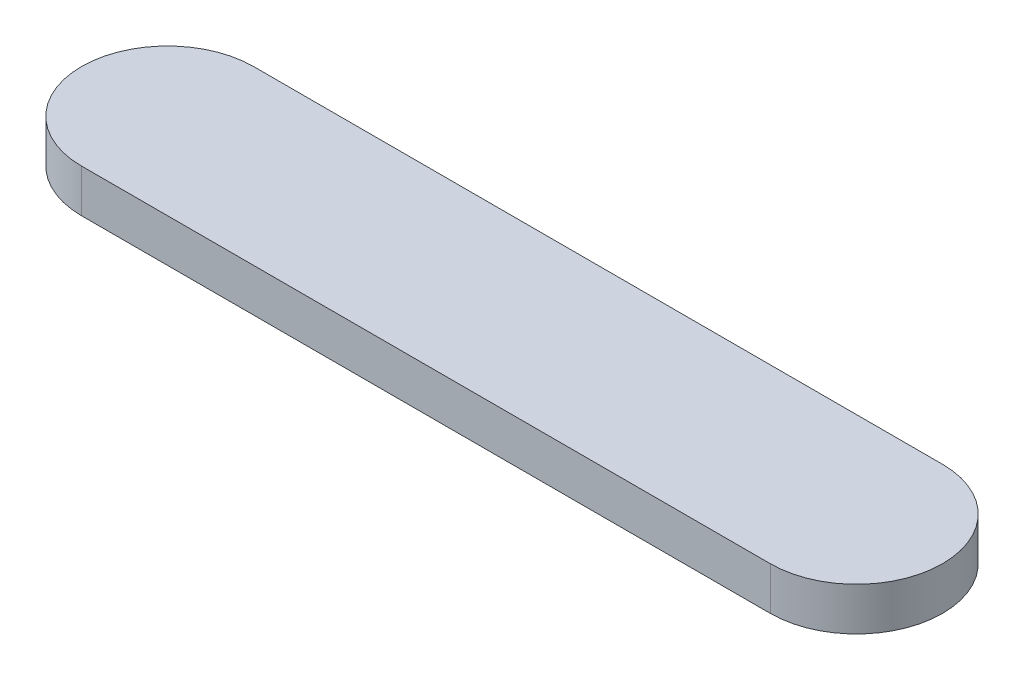
SolidWorks part; units mm, degrees
ref_plane "前视基准面" through (0, 0, 0) normal (0, 0, 1) x (1, 0, 0)
ref_plane "上视基准面" through (0, 0, 0) normal (0, 1, 0) x (1, 0, 0)
ref_plane "右视基准面" through (0, 0, 0) normal (1, 0, 0) x (0, 0, -1)
other "Configuration Table"
sketch "草图1" plane through (0, 0, 0) normal (0, 1, 0) x (1, 0, 0)
  line L0 (-200, 0) -> (200, 0) construction
  line L1 (-200, 50) -> (200, 50)
  line L2 (-200, -50) -> (200, -50)
  arc A0 (-200, 50) -> (-200, -50) centre (-200, 0) ccw
  arc A1 (200, -50) -> (200, 50) centre (200, 0) ccw
  point P2 (0, 0)
  dimension "D1" = 400
  dimension "D2" = 50
extrude "凸台-拉伸1" add sketch "草图1" along normal blind 25
